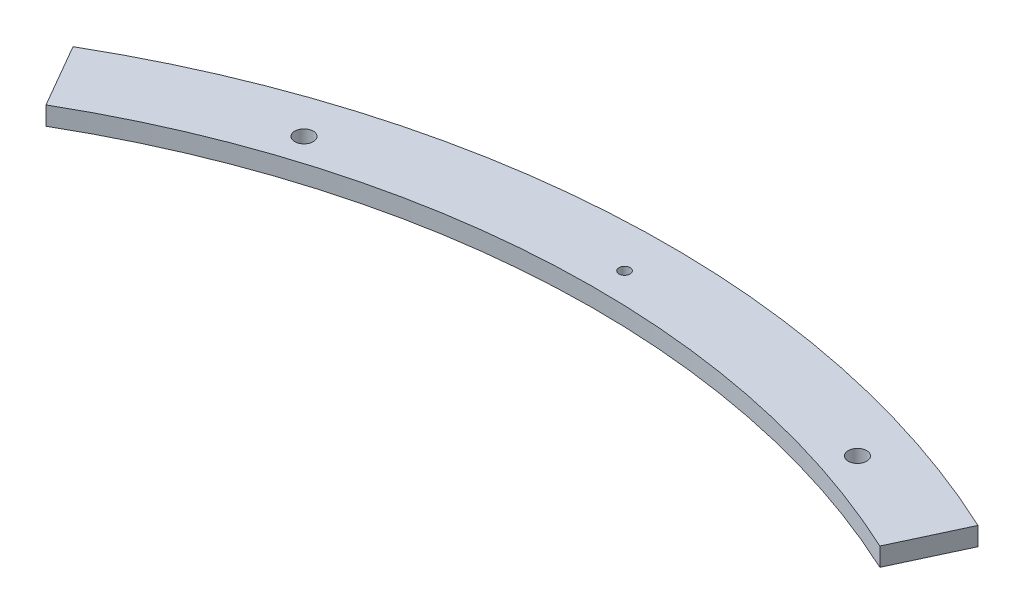
SolidWorks part; units mm, degrees
ref_plane "Front Plane" through (0, 0, 0) normal (0, 0, 1) x (1, 0, 0)
ref_plane "Top Plane" through (0, 0, 0) normal (0, 1, 0) x (1, 0, 0)
ref_plane "Right Plane" through (0, 0, 0) normal (1, 0, 0) x (0, 0, -1)
sketch "Sketch1" plane through (0, 0, 0) normal (0, 1, 0) x (1, 0, 0)
  circle A0 centre (0, 0) radius 254.5
  circle A1 centre (0, 0) radius 234.5
extrude "Boss-Extrude1" add sketch "Sketch1" along normal blind 5
sketch "Sketch2" plane through (0, 5, 0) normal (0, 1, 0) x (1, 0, 0)
  line L0 (-254.5, 0) -> (-226.6942, 0)
  line L1 (-226.6942, 0) -> (-226.6942, 60)
  line L2 (-226.6942, 60) -> (-254.5, 60)
  line L3 (-254.5, 60) -> (-254.5, 0)
  circle A0 centre (0, 0) radius 254.5 construction
  circle A1 centre (0, 0) radius 234.5 construction
  dimension "D1" = 60
extrude "Cut-Extrude1" cut sketch "Sketch2" against normal blind 5
mirror "Mirror1" about plane through (0, 0, 0) normal (0, 0, 1) of "Cut-Extrude1"
sketch "Sketch3" plane through (0, 5, 0) normal (0, 1, 0) x (1, 0, 0)
  circle A0 centre (242.5, 0) radius 2.5
  circle A1 centre (196.1866, -142.5379) radius 2.5
  circle A2 centre (74.9366, -230.6312) radius 2.5
  circle A3 centre (-74.9366, -230.6312) radius 2.5
  circle A4 centre (-196.1866, -142.5379) radius 2.5
  circle A5 centre (-242.5, 0) radius 2.5
  circle A6 centre (-196.1866, 142.5379) radius 2.5
  circle A7 centre (-74.9366, 230.6312) radius 2.5
  circle A8 centre (74.9366, 230.6312) radius 2.5
  circle A9 centre (196.1866, 142.5379) radius 2.5
  point P23 (0, 0)
  dimension "D1" = 242.5
  dimension "D2" = 10
extrude "Cut-Extrude2" cut sketch "Sketch3" against normal blind 5
sketch "Sketch4" plane through (0, 5, 0) normal (0, 1, 0) x (1, 0, 0)
  arc A0 (196.1866, 142.5379) -> (242.5, 0) centre (0, 0) cw
  circle A1 centre (230.6312, 74.9366) radius 1.5
  circle A2 centre (230.6312, -74.9366) radius 1.5
  circle A3 centre (142.5379, -196.1866) radius 1.5
  circle A4 centre (0, -242.5) radius 1.5
  circle A5 centre (-142.5379, -196.1866) radius 1.5
  circle A6 centre (-230.6312, -74.9366) radius 1.5
  circle A7 centre (-230.6312, 74.9366) radius 1.5
  circle A8 centre (-142.5379, 196.1866) radius 1.5
  circle A9 centre (0, 242.5) radius 1.5
  circle A10 centre (142.5379, 196.1866) radius 1.5
  circle A11 centre (230.6312, -74.9366) radius 1.5
  circle A12 centre (142.5379, -196.1866) radius 1.5
  circle A13 centre (0, -242.5) radius 1.5
  circle A14 centre (-142.5379, -196.1866) radius 1.5
  circle A15 centre (-230.6312, -74.9366) radius 1.5
  circle A16 centre (-230.6312, 74.9366) radius 1.5
  circle A17 centre (-142.5379, 196.1866) radius 1.5
  circle A18 centre (0, 242.5) radius 1.5
  circle A19 centre (142.5379, 196.1866) radius 1.5
  point P28 (0, 0)
  point P47 (0, 0)
  dimension "D1" = 10
  dimension "D2" = 10
extrude "Cut-Extrude3" cut sketch "Sketch4" against normal blind 5 contours A4 | A5 | A6 | A7 | A8 | A9 | A10 | A1 | A2 | A3
sketch "Sketch5" plane through (0, 5, 0) normal (0, 1, 0) x (1, 0, 0)
  line L1 (254.5, 0) -> (-396.7126, 0)
  line L2 (254.5, 0) -> (254.5, -357.2264)
  line L3 (254.5, -357.2264) -> (-396.7126, -357.2264)
  line L4 (-396.7126, 0) -> (-396.7126, -357.2264)
  arc A0 (-247.3262, -60) -> (-247.3262, 60) centre (0, 0) ccw construction
extrude "Cut-Extrude4" cut sketch "Sketch5" against normal blind 10
sketch "Sketch6" plane through (0, 5, 0) normal (0, 1, 0) x (1, 0, 0)
  line L0 (254.5, 0) -> (0, 0)
  line L1 (0, 0) -> (-127.25, 220.4035)
  line L2 (0, 0) -> (-254.5, 0)
  arc A0 (-127.25, 220.4035) -> (254.5, 0) centre (0, 0) cw
  arc A1 (254.5, 0) -> (-247.3262, 60) centre (0, 0) ccw construction
  arc A2 (-127.25, 220.4035) -> (-254.5, 0) centre (0, 0) ccw
  arc M5 (254.5, 0) -> (-247.3262, 60) centre (0, 0) ccw
  line M6 (-247.3262, 60) -> (-226.6942, 60)
  arc M7 (-226.6942, 60) -> (234.5, 0) centre (0, 0) cw
  circle M13 centre (-142.5379, 196.1866) radius 1.5
  circle M14 centre (-230.6312, 74.9366) radius 1.5
  circle M18 centre (-196.1866, 142.5379) radius 2.5
  dimension "D1" = 120
extrude "Cut-Extrude9" cut sketch "Sketch6" against normal blind 10 contours L1 M7 M5 M6 M13 M18 M14 | A2 L2 L1 M6 M7
sketch "Sketch7" plane through (0, 5, 0) normal (0, 1, 0) x (1, 0, 0)
  line L0 (254.5, 0) -> (0, 0)
  line L1 (0, 0) -> (107.5563, 230.6553)
  arc A0 (107.5563, 230.6553) -> (254.5, 0) centre (0, 0) cw
  arc A1 (254.5, 0) -> (-127.25, 220.4035) centre (0, 0) ccw construction
  dimension "D1" = 65
extrude "Cut-Extrude10" cut sketch "Sketch7" against normal blind 10
